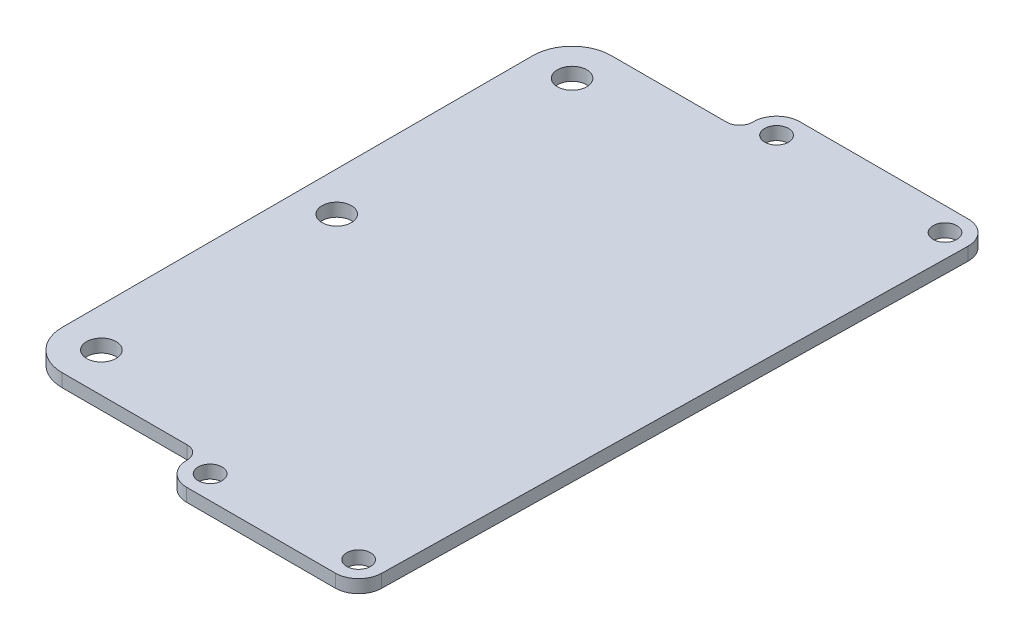
SolidWorks part; units mm, degrees
ref_plane "Front Plane" through (0, 0, 0) normal (0, 0, 1) x (1, 0, 0)
ref_plane "Top Plane" through (0, 0, 0) normal (0, 1, 0) x (1, 0, 0)
ref_plane "Right Plane" through (0, 0, 0) normal (1, 0, 0) x (0, 0, -1)
sketch "Sketch1" plane through (0, 144.9046, 0) normal (0, 1, 0) x (1, 0, 0)
  line L0 (-83.9231, -1144.8675) -> (-31.4818, -1144.8675) construction
  line L1 (-83.9231, -1144.8675) -> (-81.3145, -1296.1832) construction
  line L2 (-81.3145, -1296.1832) -> (-34.0904, -1296.1832) construction
  line L4 (-78.1495, -1144.8675) -> (-37.2554, -1144.8675)
  line L5 (-83.8236, -1150.6403) -> (-83.7683, -1153.8503)
  line L6 (-75.7364, -1296.1832) -> (-39.6684, -1296.1832)
  line L7 (-31.5813, -1150.6403) -> (-31.6366, -1153.8503) construction
  line L8 (9.0869, -1220.5253) -> (9.0869, -1163.3753) construction
  line L9 (-0.4381, -1153.8503) -> (-31.6366, -1153.8503) construction
  line L10 (9.0869, -1220.5253) -> (9.0869, -1163.3753) construction
  line L11 (-0.4381, -1153.8503) -> (-31.6366, -1153.8503) construction
  line L12 (-114.9668, -1220.5253) -> (-0.4381, -1220.5253) construction
  line L13 (-114.9668, -1220.5253) -> (-0.4381, -1220.5253) construction
  line L14 (-81.4693, -1287.2003) -> (-81.4106, -1290.606)
  line L15 (-0.4381, -1287.2003) -> (-33.9356, -1287.2003) construction
  line L16 (9.0869, -1220.5253) -> (9.0869, -1277.6753) construction
  line L17 (-57.7024, -1112.5753) -> (-57.7024, -1328.4753) construction
  line L18 (-57.7024, -1112.5753) -> (-57.7024, -1328.4753) construction
  line L19 (-114.9668, -1153.8503) -> (-83.7683, -1153.8503)
  line L20 (-124.4918, -1220.5253) -> (-124.4918, -1277.6753)
  line L21 (-124.4918, -1220.5253) -> (-124.4918, -1163.3753)
  line L22 (-114.9668, -1287.2003) -> (-81.4693, -1287.2003)
  line L23 (-33.9356, -1287.2003) -> (-33.9943, -1290.606) construction
  line L25 (-31.5813, -1150.6403) -> (-33.9943, -1290.606)
  circle A0 centre (-0.4381, -1163.3753) radius 9.525 construction
  arc A1 (9.0869, -1163.3753) -> (-0.4381, -1153.8503) centre (-0.4381, -1163.3753) ccw construction
  arc A2 (9.0869, -1277.6753) -> (-0.4381, -1287.2003) centre (-0.4381, -1277.6753) cw construction
  arc A3 (-124.4918, -1163.3753) -> (-114.9668, -1153.8503) centre (-114.9668, -1163.3753) cw
  arc A4 (-124.4918, -1277.6753) -> (-114.9668, -1287.2003) centre (-114.9668, -1277.6753) ccw
  arc A5 (-37.2554, -1144.8675) -> (-31.5813, -1150.6403) centre (-37.2554, -1150.5425) cw
  arc A6 (-78.1495, -1144.8675) -> (-83.8236, -1150.6403) centre (-78.1495, -1150.5425) ccw
  arc A7 (-39.6684, -1296.1832) -> (-33.9943, -1290.606) centre (-39.6684, -1290.5082) ccw
  arc A8 (-81.4106, -1290.606) -> (-75.7364, -1296.1832) centre (-75.7364, -1290.5082) ccw
  circle A9 centre (-39.6684, -1290.5082) radius 5.675 construction
  dimension "D1" = 57.15
extrude "Boss-Extrude1" add sketch "Sketch1" against normal up to vertex (16.002 mm away) from vertex at -12.827 contours L20 A4 L22 L14 L6 L23 L15 A2 L16 L10 A1 L11 L7 L4 L5 L19 A3 L21
hole_wizard "M5 Clearance Hole1" positions "Sketch2" profile "Sketch3" hole size "M5" standard "ANSI Metric" end condition through all
sketch "Sketch2" plane through (0, 128.9026, 0) normal (0, -1, 0) x (-1, 0, 0)
  point P0 (39.6684, -1290.5082)
  point P3 (75.7364, -1290.5082)
  point P6 (37.2554, -1150.5425)
  point P9 (78.1495, -1150.5425)
sketch "Sketch3" plane through (-39.6684, 128.9026, 1290.5082) normal (1, 0, 0) x (0, 0, -1)
  line L0 (0, 0) -> (0, 3.175)
  line L1 (0, 3.175) -> (2.9, 3.175)
  line L2 (2.9, 3.175) -> (2.9, 0)
  line L5 (2.9, 0) -> (0, 0)
  line L11 (0, -6.35) -> (0, 107.95) construction
  dimension "Thru Hole Dia." = 5.8
  dimension "Thru Hole Depth" = 3.175
hole_wizard "1/4 Clearance Hole1" positions "Sketch4" profile "Sketch5" hole size "1/4" standard "ANSI Inch" end condition through all
sketch "Sketch4" plane through (0, 132.0776, 0) normal (0, 1, 0) x (1, 0, 0)
  line L0 (-114.9668, -1220.5253) -> (-0.4381, -1220.5253) construction
  line L1 (-114.9668, -1220.5253) -> (-0.4381, -1220.5253) construction
  line L2 (-57.7024, -1112.5753) -> (-57.7024, -1328.4753) construction
  line L3 (-57.7024, -1112.5753) -> (-57.7024, -1328.4753) construction
  point P7 (-0.4381, -1163.3753)
  point P11 (-0.4381, -1220.5253)
  point P18 (-0.4381, -1277.6753)
  point P22 (-114.9668, -1163.3753)
  point P23 (-114.9668, -1220.5253)
  point P24 (-114.9668, -1277.6753)
sketch "Sketch5" plane through (-0.4381, 132.0776, 1163.3753) normal (1, 0, 0) x (0, 0, 1)
  line L0 (0, 0) -> (0, 3.175)
  line L1 (0, 3.175) -> (3.5712, 3.175)
  line L2 (3.5712, 3.175) -> (3.5712, 0)
  line L5 (3.5712, 0) -> (0, 0)
  line L11 (0, -6.35) -> (0, 107.95) construction
  dimension "Thru Hole Dia." = 7.1425
  dimension "Thru Hole Depth" = 3.175
fillet "Fillet1" radius 3.175 2 edges at (-81.4693, 130.4901, 1287.2003) (-83.7683, 130.4901, 1153.8503)
